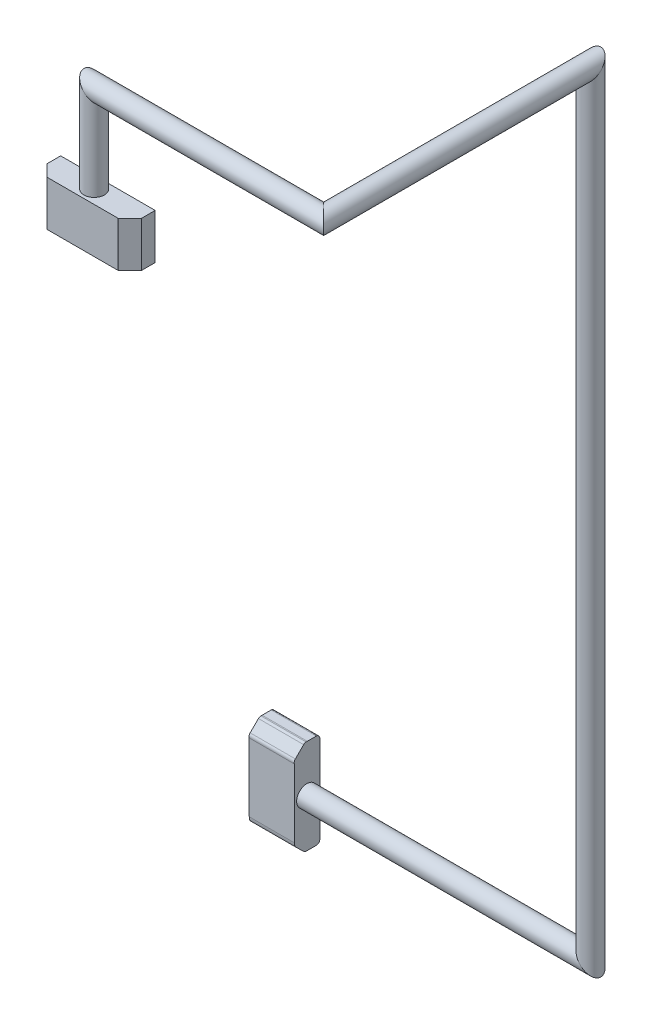
SolidWorks part; units mm, degrees
ref_plane "Plan de face" through (0, 0, 0) normal (0, 0, 1) x (1, 0, 0)
ref_plane "Plan de dessus" through (0, 0, 0) normal (0, 1, 0) x (1, 0, 0)
ref_plane "Plan de droite" through (0, 0, 0) normal (1, 0, 0) x (0, 0, -1)
sketch3d "Esquisse3D1"
  line L0 (0, 0, 0) -> (20.71, 0, 0)
  line L1 (20.71, 0, 0) -> (20.71, 56.56, 0)
  line L2 (20.71, 56.56, 0) -> (20.71, 56.56, 19.48)
  line L3 (20.71, 56.56, 19.48) -> (3.95, 56.56, 19.48)
  line L4 (3.95, 56.56, 19.48) -> (3.95, 50.06, 19.48)
  dimension "D1" = 20.71
  dimension "D2" = 6.5
  dimension "D3" = 56.56
  dimension "D4" = 19.48
  dimension "D5" = 16.76
sketch "Esquisse1" plane through (0, 0, 0) normal (1, 0, 0) x (0, 0, -1)
  circle A0 centre (0, 0) radius 0.75
  dimension "D1" = 1.5
sweep "Balayage1" add profiles "Esquisse1" path "Esquisse3D1"
sketch "Esquisse2" plane through (0, 0, 0) normal (-1, 0, 0) x (0, 0, 1)
  line L0 (-0.6936, 3.411) -> (-0.0336, 3.411)
  line L1 (-0.0336, 3.411) -> (0.0529, 3.4108)
  line L2 (0.2371, 3.3343) -> (0.8403, 2.7311)
  line L3 (0.9166, 2.4508) -> (0.9078, -2.5442)
  line L4 (0.8403, -2.8295) -> (0.2297, -3.426)
  line L5 (0.0529, -3.4992) -> (-0.6836, -3.4992)
  line L6 (-0.9436, -3.2392) -> (-0.9436, 3.1428)
  arc A0 (0.0529, 3.4108) -> (0.2371, 3.3343) centre (0.0524, 3.1495) cw
  arc A1 (0.8403, 2.7311) -> (0.9166, 2.4508) centre (0.6334, 2.5242) cw
  arc A2 (0.9078, -2.5442) -> (0.8403, -2.8295) centre (0.2663, -2.5431) cw
  arc A3 (0.2297, -3.426) -> (0.0529, -3.4992) centre (0.0499, -3.2419) cw
  arc A4 (-0.6836, -3.4992) -> (-0.9436, -3.2392) centre (-0.6836, -3.2392) cw
  arc A5 (-0.9436, 3.1428) -> (-0.6936, 3.411) centre (-0.6747, 3.1428) cw
extrude "Boss.-Extru.1" add sketch "Esquisse2" along normal blind 3.3 contours L0 L1 A0 L2 A1 L3 A2 L4 A3 L5 A4 L6 A5
sketch "Esquisse8" plane through (0, 50.06, 0) normal (0, -1, 0) x (1, 0, 0)
  line L0 (0.6361, 18.8569) -> (7.5161, 18.8569)
  line L1 (7.5261, 18.8469) -> (7.5261, 17.8596)
  line L2 (7.5213, 17.8548) -> (6.6806, 17.0099)
  line L3 (6.6735, 17.007) -> (1.4787, 17.007)
  line L4 (1.4787, 17.007) -> (0.6338, 17.8477)
  line L6 (0.6261, 17.8596) -> (0.6261, 18.8469)
  line L7 (3.95, 18.73) -> (19.96, 18.73) construction
  line L8 (0.6261, 19.6004) -> (0.6261, 18.6131)
  line L9 (1.4787, 20.453) -> (0.6338, 19.6123)
  line L10 (6.6735, 20.453) -> (1.4787, 20.453)
  line L11 (7.5213, 19.6052) -> (6.6806, 20.4501)
  line L12 (7.5261, 18.6131) -> (7.5261, 19.6004)
  line L13 (0.6361, 18.6031) -> (7.5161, 18.6031)
  arc A0 (7.5161, 18.8569) -> (7.5261, 18.8469) centre (7.5161, 18.8469) cw
  arc A1 (7.5261, 17.8596) -> (7.5213, 17.8548) centre (7.5213, 17.8596) cw
  arc A2 (6.6806, 17.0099) -> (6.6735, 17.007) centre (6.6735, 17.0169) cw
  arc A3 (0.6338, 17.8477) -> (0.6261, 17.8596) centre (0.6577, 17.8717) cw
  arc A4 (0.6261, 18.8469) -> (0.6361, 18.8569) centre (0.6361, 18.8469) cw
  arc A5 (0.6338, 19.6123) -> (0.6261, 19.6004) centre (0.6577, 19.5883) ccw
  arc A6 (6.6806, 20.4501) -> (6.6735, 20.453) centre (6.6735, 20.4431) ccw
  arc A7 (7.5261, 19.6004) -> (7.5213, 19.6052) centre (7.5213, 19.6004) ccw
  arc A8 (7.5161, 18.6031) -> (7.5261, 18.6131) centre (7.5161, 18.6131) ccw
  arc A9 (0.6261, 18.6131) -> (0.6361, 18.6031) centre (0.6361, 18.6131) ccw
extrude "Boss.-Extru.2" add sketch "Esquisse8" along normal blind 3.3 contours L8 A9 L13 A8 L12 A7 L11 A6 L10 L9 A5
